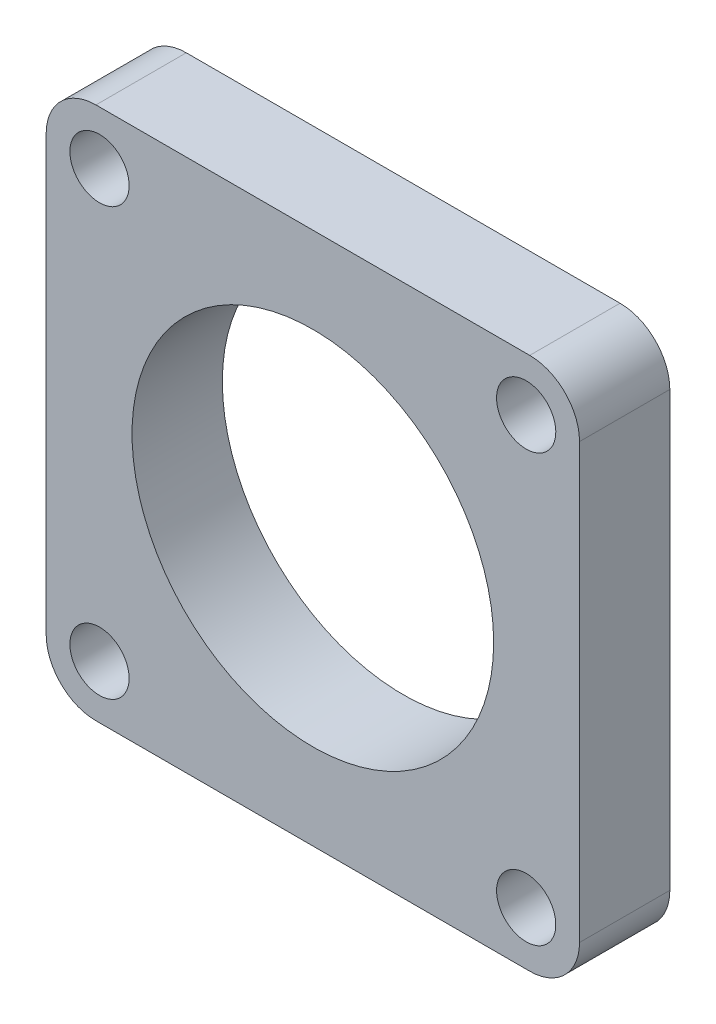
SolidWorks part; units mm, degrees
ref_plane "Front" through (0, 0, 0) normal (0, 0, 1) x (1, 0, 0)
ref_plane "Top" through (0, 0, 0) normal (0, 1, 0) x (1, 0, 0)
ref_plane "Right" through (0, 0, 0) normal (1, 0, 0) x (0, 0, -1)
sketch "Sketch1" plane through (0, 0, 0) normal (0, 0, 1) x (1, 0, 0)
  line L1 (-37.5, -37.5) -> (37.5, -37.5)
  line L2 (-37.5, -37.5) -> (-37.5, 37.5)
  line L3 (-37.5, 37.5) -> (37.5, 37.5)
  line L4 (37.5, -37.5) -> (37.5, 37.5)
  line L5 (-37.5, -37.5) -> (37.5, 37.5) construction
  line L6 (-37.5, 37.5) -> (37.5, -37.5) construction
  point P0 (0, 0)
  dimension "D1" = 75
  dimension "D2" = 75
extrude "Boss-Extrude1" add sketch "Sketch1" along normal blind 12.7
fillet "Fillet1" radius 7 4 edges at (-37.5, -37.5, 6.35) (37.5, -37.5, 6.35) (-37.5, 37.5, 6.35) (37.5, 37.5, 6.35)
sketch "Sketch2" plane through (0, 0, 12.7) normal (0, 0, 1) x (1, 0, 0)
  circle A0 centre (0, 0) radius 25.4254
  dimension "D1" = 50.8508
extrude "Cut-Extrude1" cut sketch "Sketch2" against normal up to next
sketch "Sketch3" plane through (0, 0, 12.7) normal (0, 0, 1) x (1, 0, 0)
  line L0 (30.5, 37.5) -> (-30.5, 37.5) construction
  line L1 (-37.5, 30.5) -> (-37.5, -30.5) construction
  circle A0 centre (-30, 30) radius 4.165
  dimension "D1" = 8.33
  dimension "D2" = 7.5
  dimension "D3" = 7.5
extrude "Cut-Extrude2" cut sketch "Sketch3" against normal up to next
pattern_circular "CirPattern1" count 4 over 360 about axis through (0, 0, 0) along (0, 0, 1) of "Cut-Extrude2"
